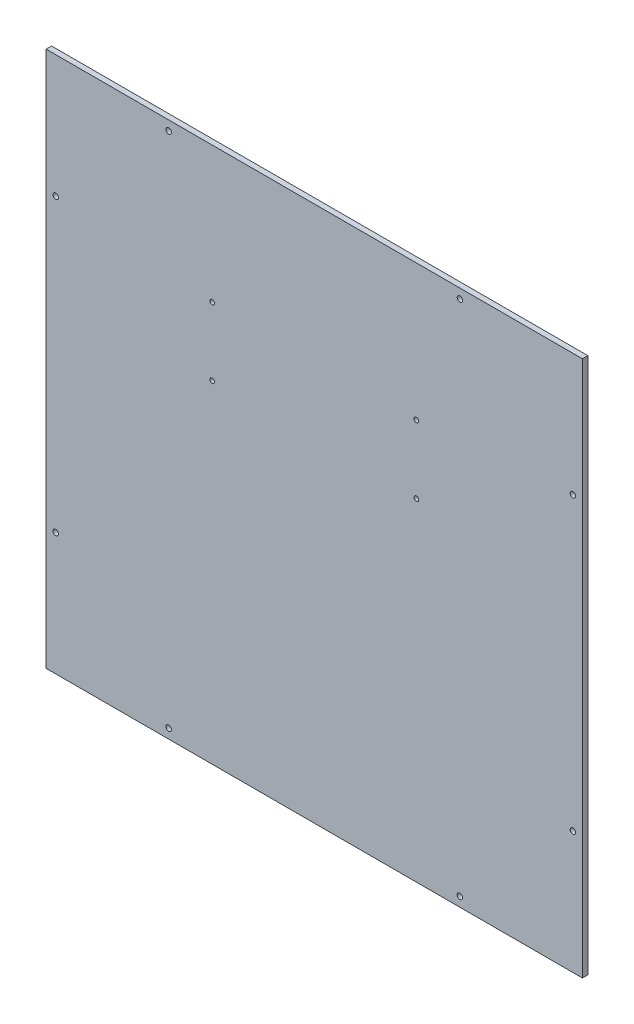
SolidWorks part; units mm, degrees
ref_plane "Piano frontale" through (0, 0, 0) normal (0, 0, 1) x (1, 0, 0)
ref_plane "Piano superiore" through (0, 0, 0) normal (0, 1, 0) x (1, 0, 0)
ref_plane "Piano destro" through (0, 0, 0) normal (1, 0, 0) x (0, 0, -1)
sketch "Schizzo1" plane through (0, 0, 0) normal (0, 0, 1) x (1, 0, 0)
  line L0 (0, 0) -> (0, 394)
  line L1 (0, 394) -> (394, 394)
  line L2 (394, 394) -> (394, 0)
  line L3 (394, 0) -> (0, 0)
  line L4 (0, 197) -> (394, 197) construction
  line L5 (197, 42) -> (197, 123.488) construction
  circle A0 centre (90, 387) radius 2
  circle A1 centre (304, 387) radius 2
  circle A2 centre (387, 304) radius 2
  circle A3 centre (7, 304) radius 2
  circle A4 centre (387, 90) radius 2
  circle A5 centre (304, 7) radius 2
  circle A6 centre (90, 7) radius 2
  circle A7 centre (7, 90) radius 2
  dimension "D3" = 4
  dimension "D4" = 7
  dimension "D6" = 7
  dimension "D5" = 90
  dimension "D1" = 394
  dimension "D2" = 394
  dimension "D7" = 90
extrude "Estrusione-Estrusione1" add sketch "Schizzo1" along normal blind 4
sketch "Schizzo2" plane through (0, 0, 4) normal (0, 0, 1) x (1, 0, 0)
  line L1 (394, 394) -> (0, 394) construction
  line L2 (197, 394) -> (197, 0) construction
  line L3 (0, 0) -> (394, 0) construction
  circle A0 centre (122, 294) radius 1.7
  circle A1 centre (122, 244) radius 1.7
  circle A2 centre (272, 294) radius 1.7
  circle A3 centre (272, 244) radius 1.7
  dimension "D1" = 150
  dimension "D2" = 100
  dimension "D3" = 3.4
  dimension "D4" = 50
extrude "Taglio-Estrusione1" cut sketch "Schizzo2" against normal through all
